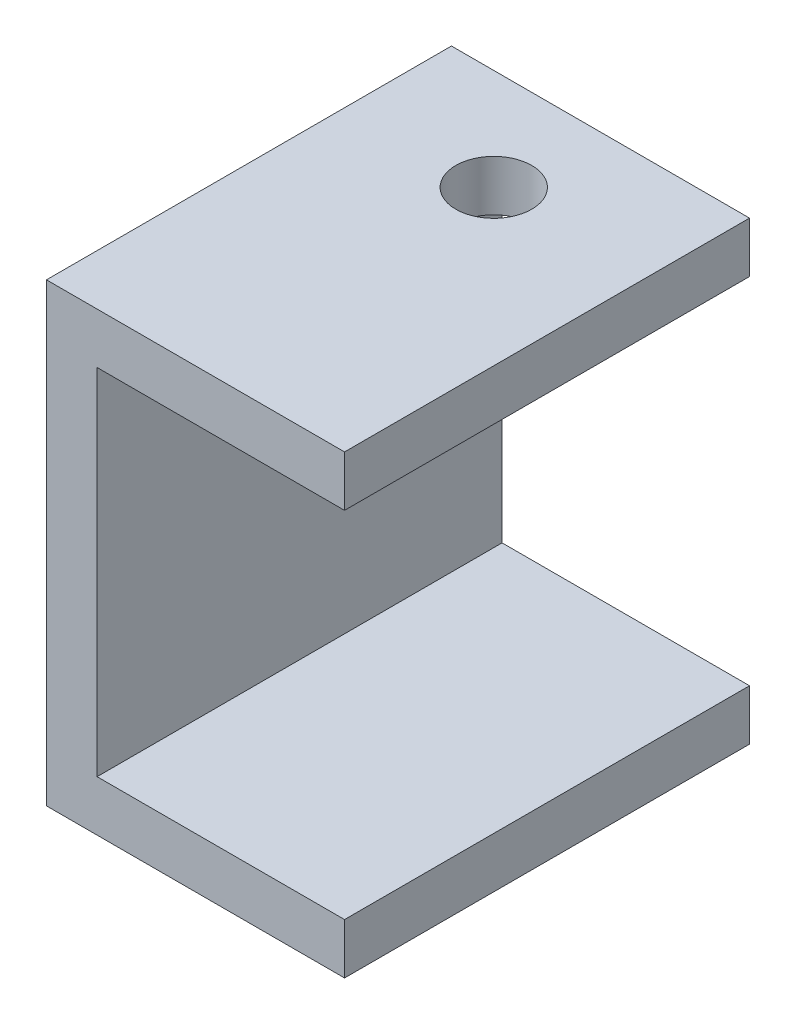
SolidWorks part; units mm, degrees
ref_plane "Front Plane" through (0, 0, 0) normal (0, 0, 1) x (1, 0, 0)
ref_plane "Top Plane" through (0, 0, 0) normal (0, 1, 0) x (1, 0, 0)
ref_plane "Right Plane" through (0, 0, 0) normal (1, 0, 0) x (0, 0, -1)
sketch "Sketch2" plane through (0, 0, 0) normal (0, 0, 1) x (1, 0, 0)
  line L0 (0, 0) -> (11.7763, 0)
  line L1 (11.7763, 0) -> (11.7763, 2)
  line L2 (11.7763, 2) -> (2, 2)
  line L3 (2, 2) -> (2, 16)
  line L4 (2, 16) -> (11.7763, 16)
  line L5 (11.7763, 16) -> (11.7763, 18)
  line L6 (11.7763, 18) -> (0, 18)
  line L7 (0, 18) -> (0, 0)
  dimension "D1" = 18
  dimension "D2" = 2
  dimension "D3" = 2
  dimension "D4" = 2
extrude "Boss-Extrude1" add sketch "Sketch2" along normal blind 16
sketch "Sketch3" plane through (0, 18, 0) normal (0, 1, 0) x (1, 0, 0)
  line L0 (5.6719, 0) -> (5.6719, -20.0921) construction
  line L1 (11.7763, 0) -> (0, 0) construction
  circle A0 centre (5.6719, -4) radius 1.5
  dimension "D1" = 4
extrude "Cut-Extrude1" cut sketch "Sketch3" against normal blind 5
